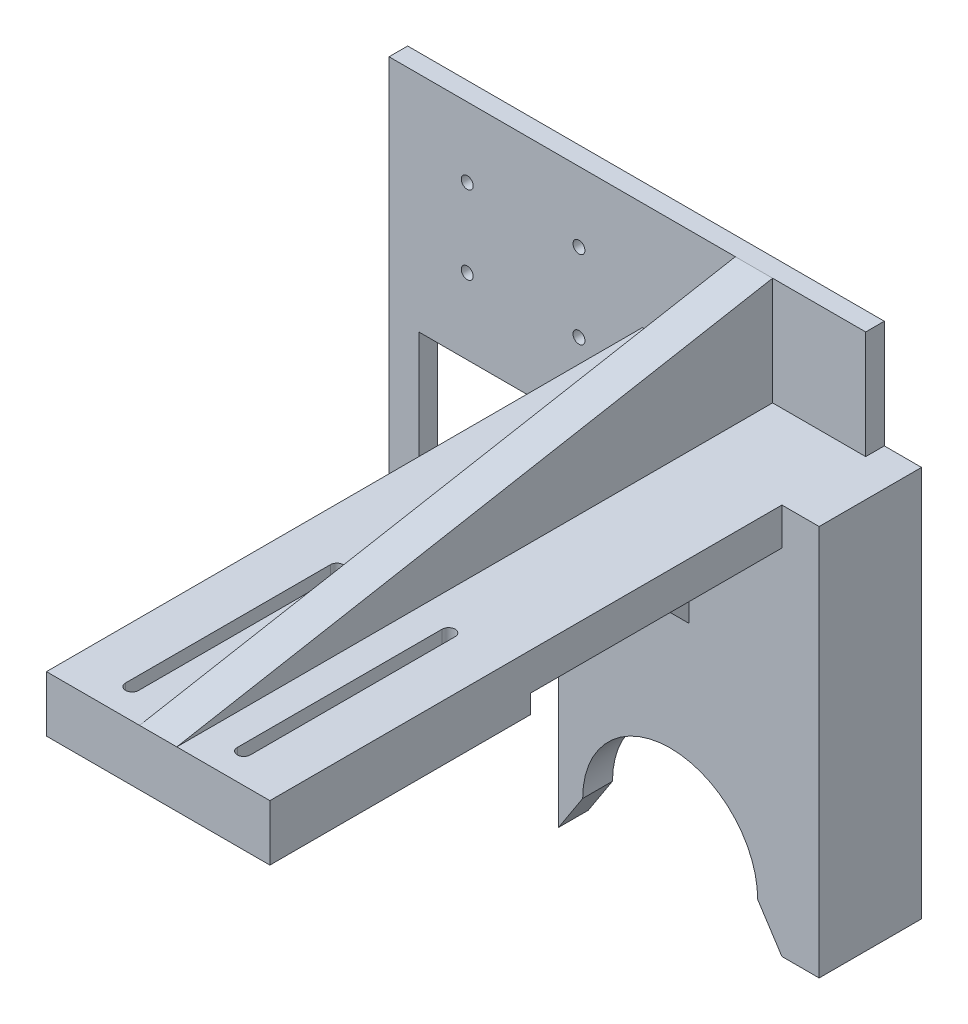
SolidWorks part; units mm, degrees
ref_plane "前视基准面" through (0, 0, 0) normal (0, 0, 1) x (1, 0, 0)
ref_plane "上视基准面" through (0, 0, 0) normal (0, 1, 0) x (1, 0, 0)
ref_plane "右视基准面" through (0, 0, 0) normal (1, 0, 0) x (0, 0, -1)
other "Configuration Table"
sketch "草图1" plane through (0, 0, 0) normal (0, 0, 1) x (1, 0, 0)
  line L0 (-25, 75) -> (-25, 25) construction
  line L2 (35, 20) -> (-85, 20)
  line L3 (35, 20) -> (35, 80)
  line L4 (35, 80) -> (-85, 80)
  line L5 (-85, 20) -> (-85, 80)
  line L6 (35, 20) -> (-85, 80) construction
  line L7 (35, 80) -> (-85, 20) construction
  point P4 (-25, 50)
  dimension "D1" = 60
  dimension "D2" = 120
extrude "凸台-拉伸1" add sketch "草图1" along normal blind 5
sketch "草图2" plane through (0, 0, 0) normal (0, 0, -1) x (-1, 0, 0)
  circle A0 centre (-25, 75) radius 1.75
  circle A1 centre (25, 75) radius 1.75
  circle A2 centre (75, 75) radius 1.75
  circle A3 centre (75, 25) radius 1.75
  circle A4 centre (25, 25) radius 1.75
  circle A5 centre (-25, 25) radius 1.75
  dimension "D1" = 3.5
  dimension "D2" = 3.5
  dimension "D3" = 3.5
  dimension "D4" = 3.5
  dimension "D5" = 3.5
  dimension "D6" = 3.5
sketch "草图3" plane through (0, 0, 5) normal (0, 0, 1) x (1, 0, 0)
  line L0 (-25, 80) -> (-25, 20) construction
  line L1 (35, 80) -> (-85, 80) construction
  line L2 (-85, 20) -> (35, 20) construction
  line L3 (35, 20) -> (35, 80) construction
  line L8 (-25, 80) -> (35, 80)
  line L9 (-25, 80) -> (-25, 72)
  line L10 (-25, 72) -> (35, 72)
  line L11 (35, 80) -> (35, 72)
  point P6 (-25, 50)
  dimension "D1" = 8
extrude "凸台-拉伸3" add sketch "草图3" along normal blind 60
sketch "草图9" plane through (0, 20, 0) normal (0, -1, 0) x (1, 0, 0)
  line L0 (-85, 0) -> (-25, 0) construction
  line L3 (-32.5, 0) -> (-41.5, 0)
  line L6 (-41.5, 0) -> (-44, 0)
  line L7 (-41.5, 35.5) -> (-41.5, 40)
  line L8 (-41.5, 40) -> (-44, 40)
  line L9 (-44, 0) -> (-44, 40)
  line L10 (-32.5, 0) -> (-30, 0)
  line L11 (-32.5, 35.5) -> (-32.5, 40)
  line L12 (-32.5, 40) -> (-30, 40)
  line L13 (-30, 0) -> (-30, 40)
  arc A0 (-41.5, 35.5) -> (-32.5, 35.5) centre (-37, 35.5) ccw
  dimension "D1" = 9
  dimension "D2" = 2.5
  dimension "D3" = 40
  dimension "D4" = 2.5
  dimension "D5" = 40
extrude "凸台-拉伸6" add sketch "草图9" along normal blind 10
sketch "草图11" plane through (0, 72, 0) normal (0, -1, 0) x (-1, 0, 0)
  circle A0 centre (-20, -52.0881) radius 1.6
  circle A1 centre (10, -28.0881) radius 1.6
  circle A2 centre (-20, -28.0881) radius 1.6
  circle A3 centre (10, -52.0881) radius 1.6
  point P3 (10, -52.0881)
  point P4 (10, -28.0881)
  point P5 (-20, -28.0881)
extrude "切除-拉伸3" cut sketch "草图11" against normal through all
sketch "草图12" plane through (0, 0, 0) normal (0, 0, -1) x (-1, 0, 0)
  line L0 (42, 67.85) -> (42, 62.85) construction
  line L1 (42, 33.65) -> (42, 38.65) construction
  line L2 (72, 33.65) -> (72, 38.65) construction
  circle A0 centre (42, 40.25) radius 1.6
  circle A1 centre (42, 61.25) radius 1.6
  arc A2 (44.1, 65.75) -> (39.9, 65.75) centre (42, 65.75) ccw construction
  arc A3 (39.9, 35.75) -> (44.1, 35.75) centre (42, 35.75) ccw construction
  circle A4 centre (72, 40.25) radius 1.6
  circle A5 centre (72, 61.25) radius 1.6
  arc A7 (69.9, 35.75) -> (74.1, 35.75) centre (72, 35.75) ccw construction
  dimension "D1" = 3.2
  dimension "D2" = 3.2
  dimension "D3" = 5
  dimension "D5" = 3.2
  dimension "D6" = 3.2
  dimension "D7" = 5
  dimension "D4" = 5
extrude "切除-拉伸4" cut sketch "草图12" against normal through all
ref_plane "基准面1" through (5, 0, 0) normal (1, 0, 0) x (0, 0, -1)
sketch "草图18" plane through (0, 0, 0) normal (0, 0, -1) x (-1, 0, 0)
  circle A0 centre (75, 75) radius 3.75
  circle A1 centre (25, 75) radius 3.75
  circle A2 centre (-25, 75) radius 3.75
  circle A3 centre (-25, 25) radius 3.75
  circle A4 centre (25, 25) radius 3.75
  circle A5 centre (75, 25) radius 3.75
  dimension "D1" = 7.5
  dimension "D2" = 7.5
  dimension "D3" = 7.5
  dimension "D4" = 7.5
  dimension "D5" = 7.5
  dimension "D6" = 7.5
extrude "切除-拉伸7" cut sketch "草图18" against normal blind 2
sketch "草图20" plane through (0, 80, 0) normal (0, 1, 0) x (1, 0, 0)
  line L0 (35, -65) -> (35, 0) construction
  line L1 (-25, -65) -> (35, -65)
  line L2 (-25, -65) -> (-25, -155)
  line L3 (-25, -155) -> (35, -155)
  line L4 (35, -65) -> (35, -155)
  dimension "D1" = 90
extrude "凸台-拉伸8" add sketch "草图20" against normal up to surface (8 mm away) up to face at (-10, 72, 50.4881)
sketch "草图22" plane through (0, 72, 0) normal (0, -1, 0) x (1, 0, 0)
  line L0 (35, 155) -> (35, 5) construction
  line L1 (-25, 155) -> (35, 155)
  line L2 (-25, 155) -> (-25, 105)
  line L3 (-25, 105) -> (35, 105)
  line L4 (35, 155) -> (35, 105)
  dimension "D1" = 50
extrude "凸台-拉伸9" add sketch "草图22" along normal blind 5
sketch "草图21" plane through (0, 80, 0) normal (0, 1, 0) x (1, 0, 0)
  line L0 (-10, -28.0881) -> (-10, -177.7445) construction
  line L1 (20, -28.0881) -> (20, -174.0966) construction
  line L3 (20, -115) -> (20, -145) construction
  line L4 (21.75, -115) -> (21.75, -145)
  line L5 (18.25, -115) -> (18.25, -145)
  line L6 (-25, -155) -> (35, -155) construction
  line L7 (5, -33) -> (5, 33) construction
  line L8 (-10, -115) -> (-10, -145) construction
  line L9 (-11.75, -115) -> (-11.75, -145)
  line L10 (-8.25, -115) -> (-8.25, -145)
  arc A0 (21.75, -115) -> (18.25, -115) centre (20, -115) ccw
  arc A1 (18.25, -145) -> (21.75, -145) centre (20, -145) ccw
  arc A2 (-11.75, -115) -> (-8.25, -115) centre (-10, -115) cw
  arc A3 (-8.25, -145) -> (-11.75, -145) centre (-10, -145) cw
  point P6 (20, -130)
  point P19 (-10, -130)
  dimension "D1" = 3.5
  dimension "D2" = 10
  dimension "D3" = 30
extrude "切除-拉伸8" cut sketch "草图21" against normal through all and the other way through all
sketch "草图23" plane through (0, 0, 5) normal (0, 0, 1) x (1, 0, 0)
  line L1 (-30, 20) -> (35, 20) construction
  line L3 (35, 20) -> (35, 72) construction
  line L5 (-25, 41) -> (35, 41)
  line L6 (-25, 41) -> (-25, 51)
  line L7 (-25, 51) -> (35, 51)
  line L8 (35, 41) -> (35, 51)
  line L9 (-25, 41) -> (35, 51) construction
  line L10 (-25, 51) -> (35, 41) construction
  point P0 (5, 46)
  dimension "D1" = 60
  dimension "D2" = 10
  dimension "D3" = 26
extrude "凸台-拉伸10" add sketch "草图23" along normal blind 160
sketch "草图24" plane through (0, 41, 0) normal (0, -1, 0) x (1, 0, 0)
  line L0 (-10, 165) -> (-10, 97.7428) construction
  line L1 (-25, 165) -> (35, 165) construction
  line L2 (-25, 165) -> (-25, 5) construction
  line L3 (-10, 157) -> (-10, 102) construction
  line L4 (-8.25, 157) -> (-8.25, 102)
  line L5 (-11.75, 157) -> (-11.75, 102)
  line L6 (5, -33) -> (5, 33) construction
  line L7 (20, 157) -> (20, 102) construction
  line L8 (18.25, 157) -> (18.25, 102)
  line L9 (21.75, 157) -> (21.75, 102)
  arc A0 (-8.25, 157) -> (-11.75, 157) centre (-10, 157) ccw
  arc A1 (-11.75, 102) -> (-8.25, 102) centre (-10, 102) ccw
  arc A2 (18.25, 157) -> (21.75, 157) centre (20, 157) cw
  arc A3 (21.75, 102) -> (18.25, 102) centre (20, 102) cw
  point P8 (-10, 129.5)
  point P17 (20, 129.5)
  dimension "D1" = 15
  dimension "D2" = 3.5
  dimension "D3" = 8
  dimension "D4" = 55
extrude "切除-拉伸9" cut sketch "草图24" against normal through all
sketch "草图25" plane through (-25, 0, 0) normal (-1, 0, 0) x (0, 0, 1)
  line L1 (5, 80) -> (155, 80)
  line L2 (5, 80) -> (5, 67)
  line L3 (5, 67) -> (155, 67)
  line L4 (155, 80) -> (155, 67)
extrude "切除-拉伸10" cut sketch "草图25" against normal through all
sketch "草图26" plane through (0, 41, 0) normal (0, -1, 0) x (1, 0, 0)
  line L0 (5, -33) -> (5, 33) construction
  line L1 (-25, 19.5) -> (35, 19.5)
  line L2 (-25, 19.5) -> (-25, 27.5)
  line L3 (-25, 27.5) -> (35, 27.5)
  line L4 (35, 19.5) -> (35, 27.5)
  line L5 (-25, 19.5) -> (35, 27.5) construction
  line L6 (-25, 27.5) -> (35, 19.5) construction
  line L7 (35, 165) -> (35, 5) construction
  line L8 (-25, 5) -> (35, 5) construction
  point P0 (5, 23.5)
  dimension "D1" = 18.5
  dimension "D2" = 8
extrude "凸台-拉伸11" add sketch "草图26" along normal blind 85
sketch "草图27" plane through (0, 0, 27.5) normal (0, 0, 1) x (1, 0, 0)
  line L0 (35, -44) -> (-25, -44) construction
  circle A0 centre (5, -44) radius 23.5
  dimension "D1" = 47
extrude "切除-拉伸11" cut sketch "草图27" against normal through all
sketch "草图28" plane through (0, 0, 27.5) normal (0, 0, 1) x (1, 0, 0)
  line L0 (35, -44) -> (35, -54)
  line L1 (35, -54) -> (28.5, -44)
  line L2 (-25, -44) -> (-25, -54)
  line L3 (-25, -54) -> (-18.5, -44)
  line L4 (-25, -44) -> (-18.5, -44)
  line L5 (28.5, -44) -> (35, -44)
  dimension "D1" = 10
extrude "凸台-拉伸12" add sketch "草图28" against normal up to surface (8 mm away) up to face at (5, -11.75, 19.5)
sketch "草图29" plane through (0, 41, 0) normal (0, -1, 0) x (1, 0, 0)
  line L0 (35, 165) -> (35, 27.5) construction
  line L1 (-25, 165) -> (35, 165)
  line L2 (-25, 165) -> (-25, 95)
  line L3 (-25, 95) -> (35, 95)
  line L4 (35, 165) -> (35, 95)
  dimension "D1" = 70
extrude "凸台-拉伸13" add sketch "草图29" along normal blind 5
sketch "草图30" plane through (0, 36, 0) normal (0, -1, 0) x (1, 0, 0)
  line L0 (5, -33) -> (5, 33) construction
  line L1 (20, 102) -> (20, 157) construction
  line L2 (18.25, 102) -> (18.25, 157)
  line L3 (21.75, 102) -> (21.75, 157)
  line L4 (-10, 102) -> (-10, 157) construction
  line L5 (-8.25, 102) -> (-8.25, 157)
  line L6 (-11.75, 102) -> (-11.75, 157)
  arc A2 (18.25, 102) -> (21.75, 102) centre (20, 102) ccw
  arc A3 (21.75, 157) -> (18.25, 157) centre (20, 157) ccw
  arc A4 (-8.25, 102) -> (-11.75, 102) centre (-10, 102) cw
  arc A5 (-11.75, 157) -> (-8.25, 157) centre (-10, 157) cw
  point P4 (-10, 129.5)
  point P10 (20, 129.5)
  dimension "D1" = 3.5
extrude "切除-拉伸12" cut sketch "草图30" against normal through all
hole_wizard "M3 十字槽沉头木螺钉的锥形沉头孔1" positions "草图31" profile "草图32" countersink size "M3" standard "GB" end condition through all
sketch "草图31" plane through (0, 0, 0) normal (0, 0, -1) x (-1, 0, 0)
  point P0 (42, 61.25)
  point P3 (72, 61.25)
  point P6 (72, 40.25)
  point P9 (42, 40.25)
sketch "草图32" plane through (-42, 61.25, 0) normal (1, 0, 0) x (0, 1, 0)
  line L0 (0, 0) -> (0, 165)
  line L1 (0, 165) -> (1.6, 165)
  line L2 (1.6, 165) -> (1.6, 1.7)
  line L3 (1.6, 1.7) -> (3.3, 0)
  line L5 (3.3, 0) -> (0, 0)
  line L6 (-1.6, 1.7) -> (-3.3, 0) construction
  line L11 (0, -6.35) -> (0, 107.95) construction
  dimension "通孔孔直径" = 3.2
  dimension "通孔孔深度" = 165
  dimension "近端锥形沉头孔直径" = 6.6
  dimension "近端锥形沉头孔角度" = 90
sketch "草图33" plane through (35, 0, 0) normal (1, 0, 0) x (0, 0, -1)
  line L1 (-19.5, 41) -> (-5, 41)
  line L2 (-19.5, 41) -> (-19.5, 20)
  line L3 (-19.5, 20) -> (-5, 20)
  line L4 (-5, 41) -> (-5, 20)
extrude "凸台-拉伸14" add sketch "草图33" against normal up to surface (60 mm away) up to face at (-25, 23, 62.4)
sketch "草图34" plane through (35, 0, 0) normal (1, 0, 0) x (0, 0, -1)
  line L0 (0, 20) -> (-19.5, 10)
  line L1 (-19.5, -54) -> (-19.5, 20) construction
  line L2 (-19.5, 10) -> (-19.5, 20)
  line L17 (0, 80) -> (-5, 80)
  line L18 (-5, 80) -> (-5, 51)
  line L19 (-5, 51) -> (-165, 51)
  line L20 (-165, 51) -> (-165, 36)
  line L21 (-165, 36) -> (-95, 36)
  line L22 (-95, 36) -> (-95, 41)
  line L23 (-95, 41) -> (-27.5, 41)
  line L24 (-27.5, 41) -> (-27.5, -54)
  line L25 (-27.5, -54) -> (-19.5, -54)
  line L26 (-19.5, -54) -> (-19.5, 20)
  line L27 (-19.5, 20) -> (0, 20)
  line L28 (0, 20) -> (0, 80)
  line L29 (0, 80) -> (-5, 80)
  line L30 (-5, 80) -> (-5, 51)
  line L31 (-5, 51) -> (-165, 51)
  line L32 (-165, 51) -> (-165, 36)
  line L33 (-165, 36) -> (-95, 36)
  line L34 (-95, 36) -> (-95, 41)
  line L35 (-95, 41) -> (-27.5, 41)
  line L36 (-27.5, 41) -> (-27.5, -54)
  line L37 (-27.5, -54) -> (-19.5, -54)
  line L38 (-19.5, -54) -> (-19.5, 20)
  line L40 (0, 20) -> (0, 80)
  line M23 (-19.5, -54) -> (-19.5, 20)
  line M24 (-19.5, 20) -> (0, 20)
  dimension "D2" = 10
  dimension "D1" = 0
extrude "凸台-拉伸15" add sketch "草图34" against normal up to surface (60 mm away) contours L0 M24 M23 up to face at (-25, 18.8, 62.4)
sketch "草图35" plane through (5, 0, 0) normal (1, 0, 0) x (0, 0, -1)
  line L6 (-57.5, 41) -> (-27.5, 11)
  line L7 (-95, 41) -> (-27.5, 41) construction
  line L8 (-27.5, -54) -> (-27.5, 41) construction
  line L9 (-27.5, 11) -> (-27.5, 41)
  line L10 (-27.5, 41) -> (-57.5, 41)
  dimension "D1" = 30
  dimension "D2" = 30
sketch "草图36" plane through (5, 0, 0) normal (1, 0, 0) x (0, 0, -1)
  line L0 (-5, 80) -> (-165, 51)
  line L1 (-165, 51) -> (-5, 51)
  line L2 (-5, 51) -> (-5, 80)
extrude "凸台-拉伸18" add sketch "草图35" along normal mid plane 10
sketch "草图37" plane through (5, 0, 0) normal (1, 0, 0) x (0, 0, -1)
  line L0 (-5, 80) -> (-165, 51)
  line L1 (-165, 51) -> (-5, 51)
  line L2 (-5, 51) -> (-5, 80)
extrude "凸台-拉伸19" add sketch "草图37" along normal mid plane 10
sketch "草图38" plane through (0, 0, 27.5) normal (0, 0, 1) x (1, 0, 0)
  line L0 (35, 51) -> (10, 51) construction
  line L1 (35, 51) -> (45, 51)
  line L2 (35, 51) -> (35, -54)
  line L3 (35, -54) -> (45, -54)
  line L4 (45, 51) -> (45, -54)
  dimension "D1" = 10
extrude "凸台-拉伸20" add sketch "草图38" against normal up to surface (8 mm away) up to face at (5, -25.4167, 19.5)
sketch "草图40" plane through (0, -54, 0) normal (0, -1, 0) x (1, 0, 0)
  line L0 (35, 19.5) -> (35, 27.5) construction
  line L1 (45, 19.5) -> (35, 19.5)
  line L2 (45, 19.5) -> (45, 0)
  line L3 (45, 0) -> (35, 0)
  line L4 (35, 19.5) -> (35, 0)
extrude "凸台-拉伸21" add sketch "草图40" against normal up to surface (105 mm away) up to face at (-10, 51, 129.5)
sketch "草图41" plane through (35, 0, 0) normal (-1, 0, 0) x (0, 0, 1)
  line L0 (0, 20) -> (19.5, 10)
  line L1 (19.5, 10) -> (19.5, -54)
  line L2 (19.5, -54) -> (0, -54)
  line L3 (0, -54) -> (0, 20)
extrude "切除-拉伸13" cut sketch "草图41" against normal blind 5
sketch "草图42" plane through (0, 0, 5) normal (0, 0, 1) x (1, 0, 0)
  line L0 (35, -54) -> (45, -54) construction
  line L1 (-85, 80) -> (-93, 80)
  line L2 (-85, 80) -> (-85, -54)
  line L3 (-85, -54) -> (-93, -54)
  line L4 (-93, 80) -> (-93, -54)
  dimension "D1" = 8
extrude "凸台-拉伸22" add sketch "草图42" against normal up to surface (5 mm away)
extrude "凸台-拉伸17" add sketch "草图36" along normal mid plane 10
